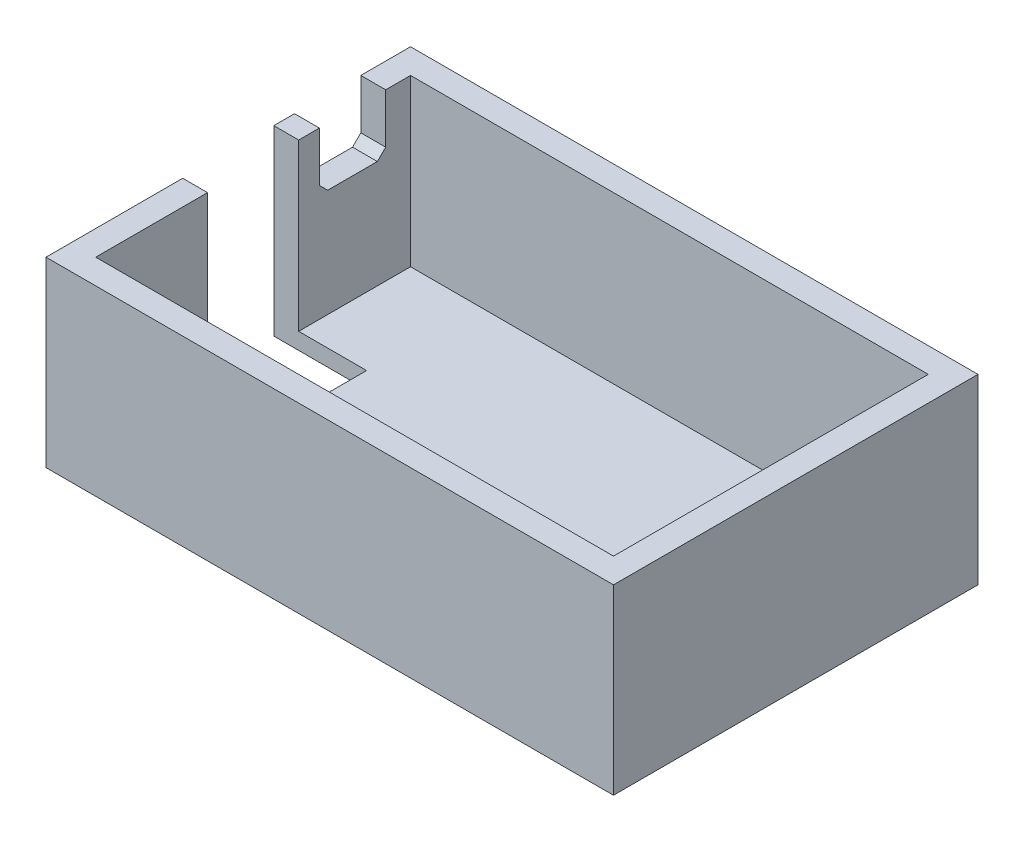
SolidWorks part; units mm, degrees
ref_plane "Front Plane" through (0, 0, 0) normal (0, 0, 1) x (1, 0, 0)
ref_plane "Top Plane" through (0, 0, 0) normal (0, 1, 0) x (1, 0, 0)
ref_plane "Right Plane" through (0, 0, 0) normal (1, 0, 0) x (0, 0, -1)
sketch "Sketch1" plane through (0, 0, 0) normal (0, 1, 0) x (1, 0, 0)
  line L0 (-33.2841, -14.3182) -> (-33.2841, -27.8182)
  line L1 (-33.2841, 10.1818) -> (29.2159, 10.1818)
  line L2 (-33.2841, 10.1818) -> (-33.2841, -3.3182)
  line L3 (-33.2841, -27.8182) -> (29.2159, -27.8182)
  line L4 (29.2159, 10.1818) -> (29.2159, -27.8182)
  line L5 (-36.2841, 13.1818) -> (32.2159, 13.1818)
  line L6 (-36.2841, 13.1818) -> (-36.2841, -3.3182)
  line L7 (-36.2841, -30.8182) -> (32.2159, -30.8182)
  line L8 (32.2159, 13.1818) -> (32.2159, -30.8182)
  line L9 (-36.2841, -3.3182) -> (-33.2841, -3.3182)
  line L11 (-36.2841, -14.3182) -> (-33.2841, -14.3182)
  line L13 (-36.2841, -14.3182) -> (-36.2841, -30.8182)
  dimension "D1" = 62.5
  dimension "D2" = 38
  dimension "D3" = 3
  dimension "D4" = 3
  dimension "D5" = 3
  dimension "D6" = 3
extrude "Boss-Extrude1" add sketch "Sketch1" along normal blind 20
sketch "Sketch2" plane through (0, 0, 0) normal (0, -1, 0) x (1, 0, 0)
  line L1 (-36.2841, -13.1818) -> (32.2159, -13.1818)
  line L2 (-36.2841, -13.1818) -> (-36.2841, 30.8182)
  line L3 (-36.2841, 30.8182) -> (32.2159, 30.8182)
  line L4 (32.2159, -13.1818) -> (32.2159, 30.8182)
extrude "Boss-Extrude2" add sketch "Sketch2" along normal blind 2
sketch "Sketch3" plane through (-36.2841, 0, 0) normal (-1, 0, 0) x (0, 0, 1)
  line L0 (30.8182, -2) -> (-13.1818, -2) construction
  line L1 (3.3182, 0) -> (14.3182, 0)
  line L2 (3.3182, 0) -> (3.3182, -2)
  line L3 (3.3182, -2) -> (14.3182, -2)
  line L4 (14.3182, 0) -> (14.3182, -2)
extrude "Cut-Extrude1" cut sketch "Sketch3" against normal blind 11.2
sketch "Sketch4" plane through (-33.2841, 0, 0) normal (1, 0, 0) x (0, 0, -1)
  line L0 (-3.3182, 20) -> (10.1818, 20) construction
  line L1 (7.1818, 20) -> (-0.8182, 20)
  line L2 (7.1818, 20) -> (7.1818, 13)
  line L3 (7.1818, 13) -> (-0.8182, 13)
  line L4 (-0.8182, 20) -> (-0.8182, 13)
  line L5 (10.1818, 20) -> (10.1818, 0) construction
  dimension "D1" = 8
  dimension "D2" = 3
  dimension "D3" = 7
extrude "Cut-Extrude2" cut sketch "Sketch4" against normal blind 10
chamfer "Chamfer2" distance 1 angle 45 2 edges at (-34.7841, 13, 0.8182) (-34.7841, 13, -7.1818)
